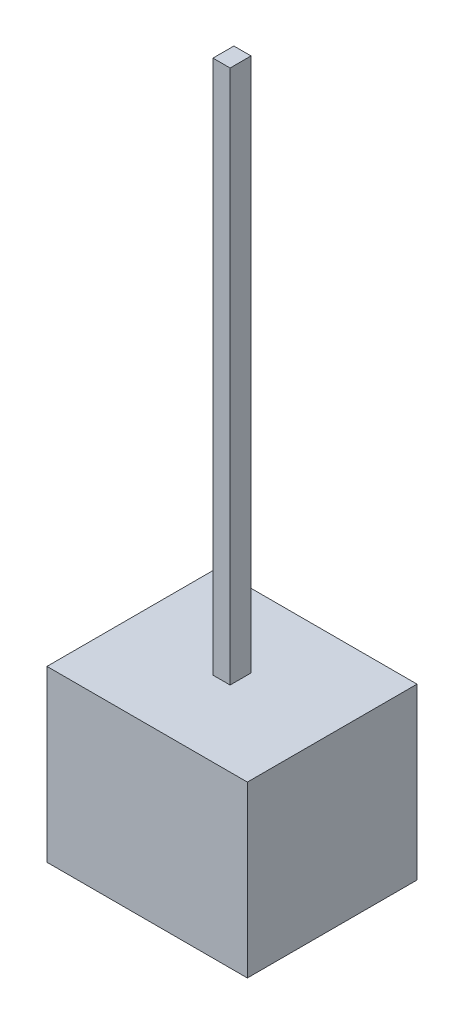
SolidWorks part; units mm, degrees
ref_plane "前视基准面" through (0, 0, 0) normal (0, 0, 1) x (1, 0, 0)
ref_plane "上视基准面" through (0, 0, 0) normal (0, 1, 0) x (1, 0, 0)
ref_plane "右视基准面" through (0, 0, 0) normal (1, 0, 0) x (0, 0, -1)
sketch "草图1" plane through (0, 0, 0) normal (1, 0, 0) x (0, 0, -1)
  line L1 (0, 0) -> (2.54, 0)
  line L2 (0, 0) -> (0, -2.54)
  line L3 (0, -2.54) -> (2.54, -2.54)
  line L4 (2.54, 0) -> (2.54, -2.54)
  dimension "D1" = 2.54
  dimension "D2" = 2.54
extrude "凸台-拉伸1" add sketch "草图1" along normal blind 3
sketch "草图2" plane through (0, 0, 0) normal (0, 1, 0) x (1, 0, 0)
  line L1 (1.3562, 1.4421) -> (1.613, 1.4421)
  line L2 (1.3562, 1.4421) -> (1.3562, 1.1288)
  line L3 (1.3562, 1.1288) -> (1.613, 1.1288)
  line L4 (1.613, 1.4421) -> (1.613, 1.1288)
extrude "凸台-拉伸2" add sketch "草图2" along normal blind 8
